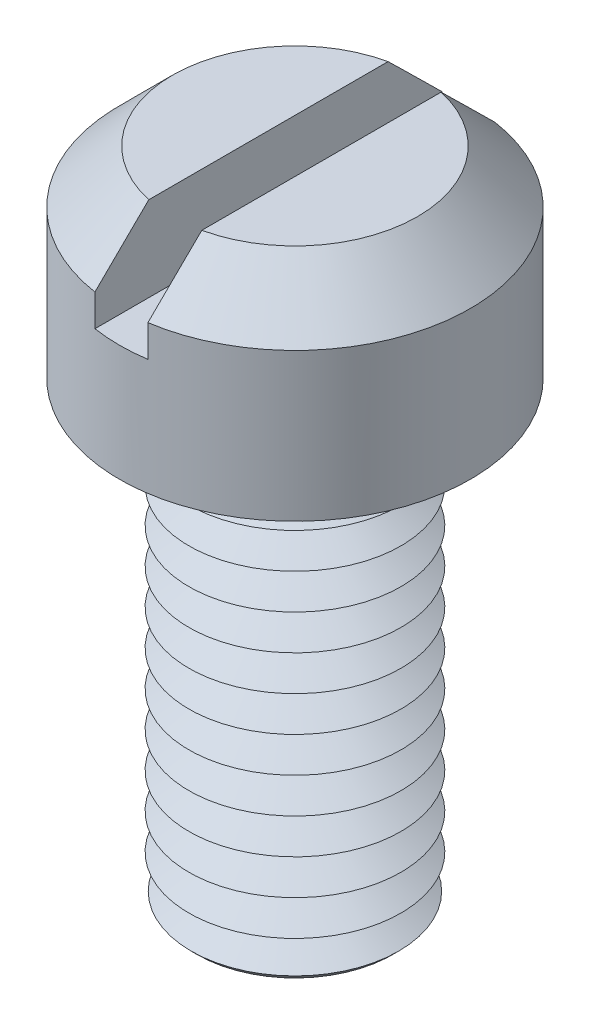
SolidWorks part; units mm, degrees
ref_plane "Front" through (0, 0, 0) normal (0, 0, 1) x (1, 0, 0)
ref_plane "Top" through (0, 0, 0) normal (0, 1, 0) x (1, 0, 0)
ref_plane "Right" through (0, 0, 0) normal (1, 0, 0) x (0, 0, -1)
ref_axis "Axis1" through (0, -50, 0) along (0, 1, 0)
sketch "Sketch ( driver )" plane through (0, 0, 0) normal (0, 0, 1) x (1, 0, 0)
  line L0 (0, 2.0708) -> (1.2626, 2.0708)
  line L1 (1.8087, 1.5247) -> (1.2626, 2.0708)
  line L2 (1.8087, 1.5247) -> (1.8087, 0)
  line L3 (1.8087, 0) -> (1.0922, 0)
  line L4 (1.0922, 0) -> (1.0922, -4.5568)
  line L5 (1.0922, -4.5568) -> (0.8738, -4.7752)
  line L6 (0.8738, -4.7752) -> (0, -4.7752)
  line L7 (0, -4.7752) -> (0, 2.0708)
  line L8 (0, 4.1777) -> (0, 2.0708) construction
  line L9 (1.0922, 0.8678) -> (1.0922, 0.5038) construction
  line L10 (1.0922, 0.5038) -> (0.7769, 0.6858) construction
  line L11 (0.7769, 0.6858) -> (1.0922, 0.8678) construction
  circle A0 centre (0, 2.0708) radius 0.2731 construction
  point P2 (0, 1.1971)
  point P12 (0.273, 2.0708)
  dimension "D2" = 45
  dimension "Length" = 4.7752
  dimension "D3" = 45
sketch "Sketch3" plane through (0, 0, 0) normal (0, 0, 1) x (1, 0, 0)
  line L8 (0, 1.1971) -> (0, -4.7752)
  line L9 (0, -4.7752) -> (0.8738, -4.7752)
  line L10 (0.8738, -4.7752) -> (1.0922, -4.5568)
  line L11 (1.0922, -4.5568) -> (1.0922, 1.1971)
  line L12 (1.0922, 1.1971) -> (0, 1.1971)
revolve "Shank Revolve ( driven )" add sketch "Sketch3" angle 360 about axis through (0, -50, 0) along (0, 1, 0)
sketch "Sketch4" plane through (0, 0, 0) normal (0, 0, 1) x (1, 0, 0)
  line L0 (0.7769, 0.6858) -> (1.0922, 0.8678)
  line L1 (1.0922, 0.8678) -> (1.6002, 0.8678)
  line L2 (1.6002, 0.8678) -> (1.6002, -5.6854)
  line L3 (0.7769, 0.6858) -> (1.0922, 0.5038)
  line L4 (1.0922, 0.5038) -> (0.7769, 0.3217)
  line L5 (0.7769, 0.3217) -> (1.0922, 0.1397)
  line L6 (1.0922, 0) -> (1.0922, -4.5568) construction
  line L7 (1.0922, 0.1397) -> (0.7769, -0.0423)
  line L8 (0.7769, -0.0423) -> (1.0922, -0.2244)
  line L9 (1.0922, -0.2244) -> (0.7769, -0.4064)
  line L10 (0.7769, -0.4064) -> (1.0922, -0.5884)
  line L11 (1.0922, -0.5884) -> (0.7769, -0.7705)
  line L12 (0.7769, -0.7705) -> (1.0922, -0.9525)
  line L13 (1.0922, -0.9525) -> (0.7769, -1.1345)
  line L14 (0.7769, -1.1345) -> (1.0922, -1.3166)
  line L15 (1.0922, -1.3166) -> (0.7769, -1.4986)
  line L16 (0.7769, -1.4986) -> (1.0922, -1.6806)
  line L17 (1.0922, -1.6806) -> (0.7769, -1.8627)
  line L18 (0.7769, -1.8627) -> (1.0922, -2.0447)
  line L19 (1.0922, -2.0447) -> (0.7769, -2.2267)
  line L20 (0.7769, -2.2267) -> (1.0922, -2.4088)
  line L21 (1.0922, -2.4088) -> (0.7769, -2.5908)
  line L22 (0.7769, -2.5908) -> (1.0922, -2.7728)
  line L23 (1.0922, -2.7728) -> (0.7769, -2.9549)
  line L24 (0.7769, -2.9549) -> (1.0922, -3.1369)
  line L25 (1.0922, -3.1369) -> (0.7769, -3.3189)
  line L26 (0.7769, -3.3189) -> (1.0922, -3.501)
  line L27 (1.0922, -3.501) -> (0.7769, -3.683)
  line L28 (0.7769, -3.683) -> (1.0922, -3.865)
  line L29 (1.0922, -3.865) -> (0.7769, -4.0471)
  line L30 (0.7769, -4.0471) -> (1.0922, -4.2291)
  line L31 (1.0922, -4.2291) -> (0.7769, -4.4111)
  line L32 (0.7769, -4.4111) -> (1.0922, -4.5932)
  line L33 (1.0922, -4.5932) -> (0.7769, -4.7752)
  line L34 (0.7769, -4.7752) -> (1.0922, -4.9572)
  line L35 (1.0922, -4.9572) -> (0.7769, -5.1393)
  line L36 (0.7769, -5.1393) -> (1.0922, -5.3213)
  line L37 (1.0922, -5.3213) -> (0.7769, -5.5033)
  line L38 (0.7769, -5.5033) -> (1.0922, -5.6854)
  line L39 (1.0922, -5.6854) -> (1.6002, -5.6854)
  dimension "D1" = 0.508
revolve "Thread Revolve Cut ( driven )" cut sketch "Sketch4" angle 360 about axis through (0, -50, 0) along (0, 1, 0)
sketch "Sketch5" plane through (0, 0, 0) normal (0, 0, 1) x (1, 0, 0)
  line L0 (0, 2.0708) -> (0, 0)
  line L1 (0, 0) -> (1.8087, 0)
  line L2 (1.8087, 0) -> (1.8087, 1.5247)
  line L3 (1.8087, 1.5247) -> (1.2626, 2.0708)
  line L4 (1.2626, 2.0708) -> (0, 2.0708)
revolve "Head Revolve ( driven )" add sketch "Sketch5" angle 360 about axis through (0, -50, 0) along (0, 1, 0)
sketch "Sketch2" plane through (0, 2.0708, 0) normal (0, 1, 0) x (-1, 0, 0)
  line L1 (0.273, -16.0765) -> (-0.273, -16.0765)
  line L2 (0.273, -16.0765) -> (0.273, 16.0765)
  line L3 (0.273, 16.0765) -> (-0.273, 16.0765)
  line L4 (-0.273, -16.0765) -> (-0.273, 16.0765)
  point P4 (-0.273, 0)
  point P5 (0, -16.0765)
extrude "Hex Cut ( driven )" cut sketch "Sketch2" against normal up to vertex (0.8738 mm away) up to point (0, 1.1971, 0)
equation "\"Thick@Sketch ( driver )\" = 0.948*\"Diam@Sketch ( driver )\""
equation "\"D1@Sketch ( driver )\" = .25 * \"Diam@Sketch ( driver )\""
equation "\"Pitch@Sketch ( driver )\" =  \"Diam@Sketch ( driver )\"/6"
equation "\"D4@Sketch ( driver )\" = .4*\"Diam@Sketch ( driver )\""
equation "\"End Chamfer@Sketch ( driver )\" = .1*\"Diam@Sketch ( driver )\""
equation "\"D5@Sketch ( driver )\" = .25 * \"Diam@Sketch ( driver )\""
equation "\"Threaded@Sketch ( driver )\" = 2.5*\"Diam@Sketch ( driver )\""
equation "\"Head Dia@Sketch ( driver )\" = 1.656 * \"Diam@Sketch ( driver )\""
